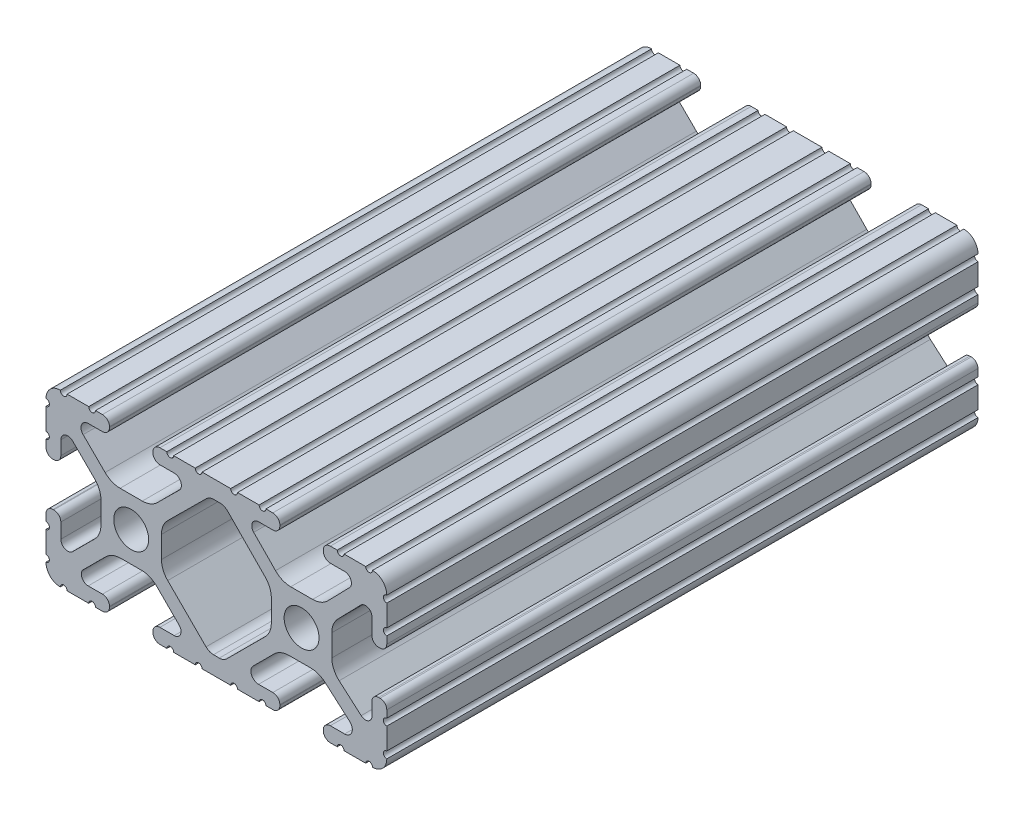
SolidWorks part; units mm, degrees
ref_plane "Front Plane" through (0, 0, 0) normal (0, 0, 1) x (1, 0, 0)
ref_plane "Top Plane" through (0, 0, 0) normal (0, 1, 0) x (1, 0, 0)
ref_plane "Right Plane" through (0, 0, 0) normal (1, 0, 0) x (0, 0, -1)
sketch "Sketch1" plane through (0, 0, 0) normal (0, 0, 1) x (1, 0, 0)
  line L0 (-7.2595, -3.8694) -> (-1.5457, -9.5728)
  line L1 (-8.1915, 1.6223) -> (-8.1915, -1.6223)
  line L2 (-1.504, 9.5765) -> (-7.252, 3.8768)
  line L3 (0.5515, 10.033) -> (-0.3952, 10.033)
  line L4 (7.2829, 3.8459) -> (1.6756, 9.5611)
  line L5 (8.1915, -1.6223) -> (8.1915, 1.6223)
  line L6 (1.5457, -9.5728) -> (7.2595, -3.8694)
  line L7 (-0.4332, -10.033) -> (0.4332, -10.033)
  line L8 (18.0171, 12.7) -> (16.9875, 12.7)
  line L9 (15.9385, 11.651) -> (15.9385, 11.5392)
  line L10 (16.9875, 10.4902) -> (19.1164, 10.4902)
  line L11 (19.8441, 8.7652) -> (16.619, 5.4551)
  line L12 (14.3449, 4.4958) -> (11.0833, 4.4958)
  line L13 (8.817, 5.4472) -> (5.5642, 8.7627)
  line L14 (6.2894, 10.4902) -> (8.4125, 10.4902)
  line L15 (9.4615, 11.5392) -> (9.4615, 11.651)
  line L16 (8.4125, 12.7) -> (7.3829, 12.7)
  line L17 (6.3669, 12.7) -> (3.1496, 12.7)
  line L18 (2.1336, 12.7) -> (-2.1336, 12.7)
  line L19 (-3.1496, 12.7) -> (-6.3669, 12.7)
  line L20 (-7.3829, 12.7) -> (-8.4125, 12.7)
  line L21 (-9.4615, 11.651) -> (-9.4615, 11.5392)
  line L22 (-8.4125, 10.4902) -> (-6.2836, 10.4902)
  line L23 (-5.5326, 8.6661) -> (-8.81, 5.4163)
  line L24 (-11.0455, 4.4958) -> (-14.3545, 4.4958)
  line L25 (-16.59, 5.4163) -> (-19.8674, 8.6661)
  line L26 (-19.1164, 10.4902) -> (-16.9875, 10.4902)
  line L27 (-15.9385, 11.5392) -> (-15.9385, 11.651)
  line L28 (-16.9875, 12.7) -> (-18.0171, 12.7)
  line L29 (-19.0331, 12.7) -> (-22.2504, 12.7)
  line L30 (-25.4, 9.5504) -> (-25.4, 6.3331)
  line L31 (-25.4, 5.3171) -> (-25.4, 4.2375)
  line L32 (-24.401, 3.2385) -> (-24.2392, 3.2385)
  line L33 (-23.1902, 4.2875) -> (-23.1902, 6.3347)
  line L34 (-21.434, 7.0665) -> (-18.148, 3.8082)
  line L35 (-17.2085, 1.5536) -> (-17.2085, -1.6952)
  line L36 (-18.1405, -3.9423) -> (-21.4316, -7.2274)
  line L37 (-23.1902, -6.498) -> (-23.1902, -4.2875)
  line L38 (-24.2392, -3.2385) -> (-24.351, -3.2385)
  line L39 (-25.4, -4.2875) -> (-25.4, -5.3171)
  line L40 (-25.4, -6.3331) -> (-25.4, -9.5504)
  line L41 (-22.2504, -12.7) -> (-19.0331, -12.7)
  line L42 (-18.0171, -12.7) -> (-16.9875, -12.7)
  line L43 (-15.9384, -11.651) -> (-15.9384, -11.5392)
  line L44 (-16.9875, -10.4902) -> (-19.1164, -10.4902)
  line L45 (-19.8341, -8.7551) -> (-16.4966, -5.4237)
  line L46 (-14.2536, -4.4958) -> (-11.1464, -4.4958)
  line L47 (-8.9034, -5.4237) -> (-5.5659, -8.7551)
  line L48 (-6.2836, -10.4902) -> (-8.4125, -10.4902)
  line L49 (-9.4616, -11.5392) -> (-9.4616, -11.651)
  line L50 (-8.4125, -12.7) -> (-7.3829, -12.7)
  line L51 (-6.3669, -12.7) -> (-3.1496, -12.7)
  line L52 (-2.1336, -12.7) -> (2.1336, -12.7)
  line L53 (3.1496, -12.7) -> (6.3669, -12.7)
  line L54 (7.3829, -12.7) -> (8.4125, -12.7)
  line L55 (9.4616, -11.651) -> (9.4616, -11.5392)
  line L56 (8.4125, -10.4902) -> (6.2894, -10.4902)
  line L57 (5.4807, -8.5353) -> (8.5979, -5.4237)
  line L58 (10.8409, -4.4958) -> (14.1026, -4.4958)
  line L59 (16.1879, -5.2766) -> (19.8682, -8.4822)
  line L60 (19.1164, -10.4902) -> (16.9875, -10.4902)
  line L61 (15.9384, -11.5392) -> (15.9384, -11.651)
  line L62 (16.9875, -12.7) -> (18.0171, -12.7)
  line L63 (19.0331, -12.7) -> (22.2504, -12.7)
  line L64 (25.4, -9.5504) -> (25.4, -6.3331)
  line L65 (25.4, -5.3171) -> (25.4, -4.2375)
  line L66 (24.401, -3.2385) -> (24.1892, -3.2385)
  line L67 (23.1902, -4.2375) -> (23.1902, -6.1559)
  line L68 (21.584, -6.8869) -> (18.2982, -4.025)
  line L69 (17.2085, -1.6308) -> (17.2085, 1.6308)
  line L70 (18.1094, 3.8465) -> (21.5263, 7.3534)
  line L71 (23.1902, 6.6769) -> (23.1902, 4.2375)
  line L72 (24.1892, 3.2385) -> (24.401, 3.2385)
  line L73 (25.4, 4.2375) -> (25.4, 5.3171)
  line L74 (25.4, 6.3332) -> (25.4, 9.5504)
  line L75 (22.2504, 12.7) -> (19.0331, 12.7)
  circle A0 centre (-12.7, 0) radius 2.6035
  circle A1 centre (12.7, 0) radius 2.6035
  arc A2 (-1.5457, -9.5728) -> (-0.4332, -10.033) centre (-0.4332, -8.4582) ccw
  arc A3 (-8.1915, -1.6223) -> (-7.2595, -3.8694) centre (-5.0165, -1.6223) ccw
  arc A4 (-7.252, 3.8768) -> (-8.1915, 1.6223) centre (-5.0165, 1.6223) ccw
  arc A5 (-0.3952, 10.033) -> (-1.504, 9.5765) centre (-0.3952, 8.4582) ccw
  arc A6 (1.6756, 9.5611) -> (0.5515, 10.033) centre (0.5515, 8.4582) ccw
  arc A7 (8.1915, 1.6223) -> (7.2829, 3.8459) centre (5.0165, 1.6223) ccw
  arc A8 (7.2595, -3.8694) -> (8.1915, -1.6223) centre (5.0165, -1.6223) ccw
  arc A9 (0.4332, -10.033) -> (1.5457, -9.5728) centre (0.4332, -8.4582) ccw
  arc A10 (18.0171, 12.7) -> (19.0331, 12.7) centre (18.5251, 12.7) ccw
  arc A11 (16.9875, 12.7) -> (15.9385, 11.651) centre (16.9875, 11.651) ccw
  arc A12 (15.9385, 11.5392) -> (16.9875, 10.4902) centre (16.9875, 11.5392) ccw
  arc A13 (19.8441, 8.7652) -> (19.1164, 10.4902) centre (19.1164, 9.4742) ccw
  arc A14 (14.3449, 4.4958) -> (16.619, 5.4551) centre (14.3449, 7.6708) ccw
  arc A15 (8.817, 5.4472) -> (11.0833, 4.4958) centre (11.0833, 7.6708) ccw
  arc A16 (6.2894, 10.4902) -> (5.5642, 8.7627) centre (6.2894, 9.4742) ccw
  arc A17 (8.4125, 10.4902) -> (9.4615, 11.5392) centre (8.4125, 11.5392) ccw
  arc A18 (9.4615, 11.651) -> (8.4125, 12.7) centre (8.4125, 11.651) ccw
  arc A19 (6.3669, 12.7) -> (7.3829, 12.7) centre (6.8749, 12.7) ccw
  arc A20 (2.1336, 12.7) -> (3.1496, 12.7) centre (2.6416, 12.7) ccw
  arc A21 (-3.1496, 12.7) -> (-2.1336, 12.7) centre (-2.6416, 12.7) ccw
  arc A22 (-7.3829, 12.7) -> (-6.3669, 12.7) centre (-6.8749, 12.7) ccw
  arc A23 (-8.4125, 12.7) -> (-9.4615, 11.651) centre (-8.4125, 11.651) ccw
  arc A24 (-9.4615, 11.5392) -> (-8.4125, 10.4902) centre (-8.4125, 11.5392) ccw
  arc A25 (-5.5326, 8.6661) -> (-6.2836, 10.4902) centre (-6.2836, 9.4235) ccw
  arc A26 (-11.0455, 4.4958) -> (-8.81, 5.4163) centre (-11.0455, 7.6708) ccw
  arc A27 (-16.59, 5.4163) -> (-14.3545, 4.4958) centre (-14.3545, 7.6708) ccw
  arc A28 (-19.1164, 10.4902) -> (-19.8674, 8.6661) centre (-19.1164, 9.4235) ccw
  arc A29 (-16.9875, 10.4902) -> (-15.9385, 11.5392) centre (-16.9875, 11.5392) ccw
  arc A30 (-15.9385, 11.651) -> (-16.9875, 12.7) centre (-16.9875, 11.651) ccw
  arc A31 (-19.0331, 12.7) -> (-18.0171, 12.7) centre (-18.5251, 12.7) ccw
  arc A32 (-23.2664, 12.6998) -> (-22.2504, 12.7) centre (-22.7584, 12.7) ccw
  arc A33 (-23.2664, 12.6998) -> (-25.3998, 10.5664) centre (-23.2918, 10.5918) ccw
  arc A34 (-25.4, 9.5504) -> (-25.3998, 10.5664) centre (-25.4, 10.0584) ccw
  arc A35 (-25.4, 5.3171) -> (-25.4, 6.3331) centre (-25.4, 5.8251) ccw
  arc A36 (-25.4, 4.2375) -> (-24.401, 3.2385) centre (-24.401, 4.2375) ccw
  arc A37 (-24.2392, 3.2385) -> (-23.1902, 4.2875) centre (-24.2392, 4.2875) ccw
  arc A38 (-21.434, 7.0665) -> (-23.1902, 6.3347) centre (-22.1596, 6.3347) ccw
  arc A39 (-17.2085, 1.5536) -> (-18.148, 3.8082) centre (-20.3835, 1.5536) ccw
  arc A40 (-18.1405, -3.9423) -> (-17.2085, -1.6952) centre (-20.3835, -1.6952) ccw
  arc A41 (-23.1902, -6.498) -> (-21.4316, -7.2274) centre (-22.1596, -6.498) ccw
  arc A42 (-23.1902, -4.2875) -> (-24.2392, -3.2385) centre (-24.2392, -4.2875) ccw
  arc A43 (-24.351, -3.2385) -> (-25.4, -4.2875) centre (-24.351, -4.2875) ccw
  arc A44 (-25.4, -6.3331) -> (-25.4, -5.3171) centre (-25.4, -5.8251) ccw
  arc A45 (-25.3998, -10.5664) -> (-25.4, -9.5504) centre (-25.4, -10.0584) ccw
  arc A46 (-25.3998, -10.5664) -> (-23.2664, -12.6998) centre (-23.2918, -10.5918) ccw
  arc A47 (-22.2504, -12.7) -> (-23.2664, -12.6998) centre (-22.7584, -12.7) ccw
  arc A48 (-18.0171, -12.7) -> (-19.0331, -12.7) centre (-18.5251, -12.7) ccw
  arc A49 (-16.9875, -12.7) -> (-15.9384, -11.651) centre (-16.9875, -11.651) ccw
  arc A50 (-15.9384, -11.5392) -> (-16.9875, -10.4902) centre (-16.9875, -11.5392) ccw
  arc A51 (-19.8341, -8.7551) -> (-19.1164, -10.4902) centre (-19.1164, -9.4742) ccw
  arc A52 (-14.2536, -4.4958) -> (-16.4966, -5.4237) centre (-14.2536, -7.6708) ccw
  arc A53 (-8.9034, -5.4237) -> (-11.1464, -4.4958) centre (-11.1464, -7.6708) ccw
  arc A54 (-6.2836, -10.4902) -> (-5.5659, -8.7551) centre (-6.2836, -9.4742) ccw
  arc A55 (-8.4125, -10.4902) -> (-9.4616, -11.5392) centre (-8.4125, -11.5392) ccw
  arc A56 (-9.4616, -11.651) -> (-8.4125, -12.7) centre (-8.4125, -11.651) ccw
  arc A57 (-6.3669, -12.7) -> (-7.3829, -12.7) centre (-6.8749, -12.7) ccw
  arc A58 (-2.1336, -12.7) -> (-3.1496, -12.7) centre (-2.6416, -12.7) ccw
  arc A59 (3.1496, -12.7) -> (2.1336, -12.7) centre (2.6416, -12.7) ccw
  arc A60 (7.3829, -12.7) -> (6.3669, -12.7) centre (6.8749, -12.7) ccw
  arc A61 (8.4125, -12.7) -> (9.4616, -11.651) centre (8.4125, -11.651) ccw
  arc A62 (9.4616, -11.5392) -> (8.4125, -10.4902) centre (8.4125, -11.5392) ccw
  arc A63 (5.4807, -8.5353) -> (6.2894, -10.4902) centre (6.2894, -9.3455) ccw
  arc A64 (10.8409, -4.4958) -> (8.5979, -5.4237) centre (10.8409, -7.6708) ccw
  arc A65 (16.1879, -5.2766) -> (14.1026, -4.4958) centre (14.1026, -7.6708) ccw
  arc A66 (19.1164, -10.4902) -> (19.8682, -8.4822) centre (19.1164, -9.3455) ccw
  arc A67 (16.9875, -10.4902) -> (15.9384, -11.5392) centre (16.9875, -11.5392) ccw
  arc A68 (15.9384, -11.651) -> (16.9875, -12.7) centre (16.9875, -11.651) ccw
  arc A69 (19.0331, -12.7) -> (18.0171, -12.7) centre (18.5251, -12.7) ccw
  arc A70 (23.2664, -12.6998) -> (22.2504, -12.7) centre (22.7584, -12.7) ccw
  arc A71 (23.2664, -12.6998) -> (25.3998, -10.5664) centre (23.2918, -10.5918) ccw
  arc A72 (25.4, -9.5504) -> (25.3998, -10.5664) centre (25.4, -10.0584) ccw
  arc A73 (25.4, -5.3171) -> (25.4, -6.3331) centre (25.4, -5.8251) ccw
  arc A74 (25.4, -4.2375) -> (24.401, -3.2385) centre (24.401, -4.2375) ccw
  arc A75 (24.1892, -3.2385) -> (23.1902, -4.2375) centre (24.1892, -4.2375) ccw
  arc A76 (21.584, -6.8869) -> (23.1902, -6.1559) centre (22.2207, -6.1559) ccw
  arc A77 (17.2085, -1.6308) -> (18.2982, -4.025) centre (20.3835, -1.6308) ccw
  arc A78 (18.1094, 3.8465) -> (17.2085, 1.6308) centre (20.3835, 1.6308) ccw
  arc A79 (23.1902, 6.6769) -> (21.5263, 7.3534) centre (22.2207, 6.6769) ccw
  arc A80 (23.1902, 4.2375) -> (24.1892, 3.2385) centre (24.1892, 4.2375) ccw
  arc A81 (24.401, 3.2385) -> (25.4, 4.2375) centre (24.401, 4.2375) ccw
  arc A82 (25.4, 6.3332) -> (25.4, 5.3171) centre (25.4, 5.8251) ccw
  arc A83 (25.3998, 10.5664) -> (25.4, 9.5504) centre (25.4, 10.0584) ccw
  arc A84 (25.3998, 10.5664) -> (23.2664, 12.6998) centre (23.2918, 10.5918) ccw
  arc A85 (22.2504, 12.7) -> (23.2664, 12.6998) centre (22.7584, 12.7) ccw
  point P248 (0, 10.033)
extrude "Boss-Extrude1" add sketch "Sketch1" along normal mid plane 88.138
